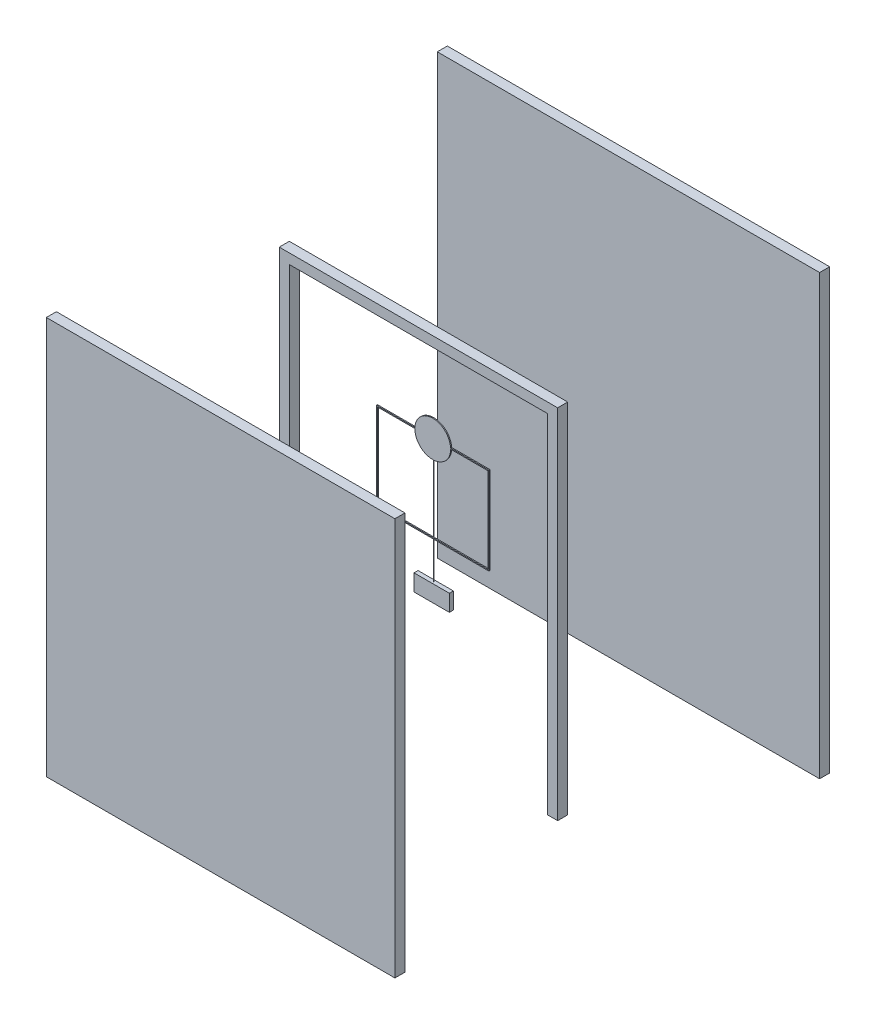
SolidWorks part; units mm, degrees
ref_plane "前视基准面" through (0, 0, 0) normal (0, 0, 1) x (1, 0, 0)
ref_plane "上视基准面" through (0, 0, 0) normal (0, 1, 0) x (1, 0, 0)
ref_plane "右视基准面" through (0, 0, 0) normal (1, 0, 0) x (0, 0, -1)
other "Configuration Table"
sketch "草图1" plane through (0, 0, 0) normal (0, 0, 1) x (1, 0, 0)
  line L0 (-66.7836, 86.4969) -> (-66.7836, -86.4969)
  line L1 (0, 0) -> (0, -75.0712) construction
  line L2 (66.7836, 86.4969) -> (66.7836, -86.4969)
  point P3 (-66.7836, 0)
extrude "拉伸-薄壁1" add sketch "草图1" along normal blind 5 thin
sketch "草图2" plane through (0, 0, 5) normal (0, 0, 1) x (1, 0, 0)
  line L0 (-69.2836, 86.4969) -> (64.2836, 86.4969)
  line L1 (-71.7836, 86.4969) -> (-66.7836, 86.4969) construction
  line L2 (61.7836, 86.4969) -> (66.7836, 86.4969) construction
  line L3 (64.2836, 86.4969) -> (66.7836, 86.4969)
  line L4 (-69.2836, 86.4969) -> (-71.7836, 86.4969)
extrude "拉伸-薄壁2" add sketch "草图2" against normal blind 5 thin thin type one direction wall 5
sketch "草图3" plane through (0, 0, 0) normal (0, 0, -1) x (-1, 0, 0)
  line L0 (0, 86.4969) -> (0, 51.5143)
  line L1 (-61.7836, 86.4969) -> (66.7836, 86.4969) construction
extrude "拉伸-薄壁3" add sketch "草图3" against normal blind 0.1 thin
sketch "草图5" plane through (0, 0, 0) normal (0, 0, -1) x (-1, 0, 0)
  circle A0 centre (-0.1, 42.5222) radius 8.9193
extrude "凸台-拉伸1" add sketch "草图5" against normal blind 0.5 separate body
sketch "草图6" plane through (0, 0, 0) normal (0, 0, -1) x (-1, 0, 0)
  line L0 (8.8193, 42.5222) -> (27.4125, 42.5222)
  line L1 (27.4125, 42.5222) -> (27.4125, 0)
  line L2 (-0.1, 86.4969) -> (-0.1, 51.5143) construction
  line L3 (-27.6125, 42.5222) -> (-27.6125, 0)
  line L4 (-9.0193, 42.5222) -> (-27.6125, 42.5222)
  line L5 (-27.6125, 0) -> (27.4125, 0)
  circle A0 centre (-0.1, 42.5222) radius 8.9193 construction
extrude "拉伸-薄壁4" add sketch "草图6" against normal blind 0.5 separate body thin thin type one direction wall 0.5
sketch "草图7" plane through (0, 0, 0) normal (0, 0, -1) x (-1, 0, 0)
  line L0 (-0.1, 33.6029) -> (-0.1, -19.3906)
  circle A0 centre (-0.1, 42.5222) radius 8.9193 construction
extrude "拉伸-薄壁6" add sketch "草图7" along normal blind 0.1 thin
sketch "草图8" plane through (0, 0, 0) normal (0, 0, -1) x (-1, 0, 0)
  line L0 (-0.2, -19.3906) -> (8.6913, -19.3906)
  line L1 (8.6913, -19.3906) -> (8.6913, -27.6457)
  line L2 (-0.1, 33.6029) -> (-0.1, -19.3906) construction
  line L3 (-8.8913, -19.3906) -> (-8.8913, -27.6457)
  line L4 (0, -19.3906) -> (-8.8913, -19.3906)
  line L5 (-8.8913, -27.6457) -> (8.6913, -27.6457)
extrude "凸台-拉伸3" add sketch "草图8" along normal mid plane 2 contours L3 L5 L1 L0 L4
ref_plane "基准面2" through (0, 0, 100) normal (0, 0, 1) x (1, 0, 0)
sketch "草图9" plane through (0, 0, 100) normal (0, 0, 1) x (1, 0, 0)
  line L0 (-90.2246, 100.6834) -> (-90.2246, -97.305)
  line L1 (-90.2246, -97.305) -> (83.2788, -97.305)
  line L2 (83.2788, -97.305) -> (83.2788, 100.6834)
  line L3 (83.2788, 100.6834) -> (-90.2246, 100.6834)
extrude "凸台-拉伸4" add sketch "草图9" along normal mid plane 5 separate body
ref_plane "基准面3" through (0, 0, -100) normal (0, 0, 1) x (1, 0, 0)
sketch "草图11" plane through (0, 0, -100) normal (0, 0, 1) x (1, 0, 0)
  line L0 (94.6753, 112.5124) -> (94.6753, -105.7475)
  line L1 (94.6753, -105.7475) -> (-95.6257, -105.7475)
  line L2 (-95.6257, -105.7475) -> (-95.6257, 112.5124)
  line L3 (-95.6257, 112.5124) -> (94.6753, 112.5124)
extrude "凸台-拉伸5" add sketch "草图11" along normal mid plane 5 separate body
